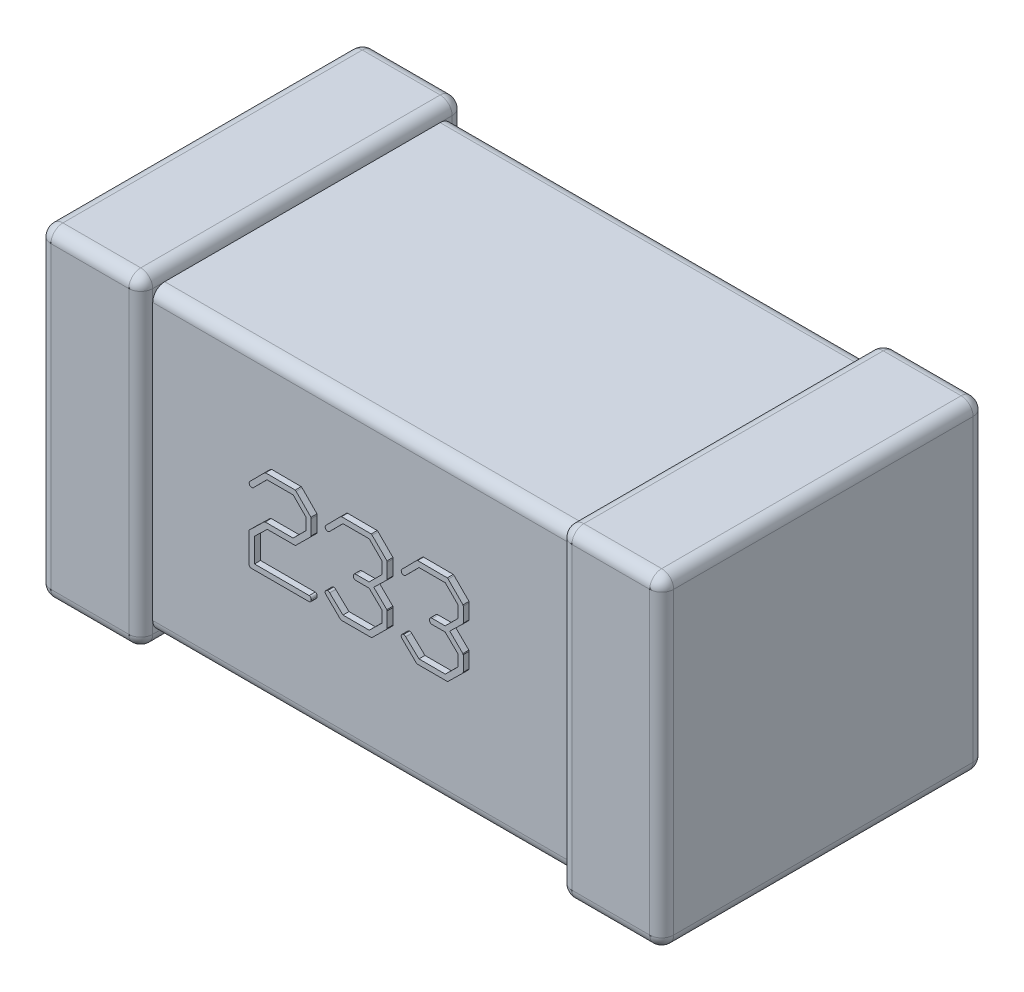
SolidWorks part; units mm, degrees
ref_plane "Front Plane" through (0, 0, 0) normal (0, 0, 1) x (1, 0, 0)
ref_plane "Top Plane" through (0, 0, 0) normal (0, 1, 0) x (1, 0, 0)
ref_plane "Right Plane" through (0, 0, 0) normal (1, 0, 0) x (0, 0, -1)
sketch "Sketch2" plane through (0, 0, 0) normal (0, 1, 0) x (1, 0, 0)
  line L1 (0, 0) -> (1, 0)
  line L2 (0, 0) -> (0, 0.5)
  line L3 (0, 0.5) -> (1, 0.5)
  line L4 (1, 0) -> (1, 0.5)
  dimension "D1" = 1
  dimension "D2" = 0.5
extrude "Boss-Extrude1" add sketch "Sketch2" along normal blind 0.5 contours L3 L4 L1 L2
fillet "Fillet3" radius 0.02 12 edges at (0, 0, -0.25) (0.5, 0, -0.5) (1, 0, -0.25) (0.5, 0, 0) (0, 0.5, -0.25) (0.5, 0.5, -0.5) (1, 0.5, -0.25) (0.5, 0.5, 0) (0, 0.25, -0.5) (1, 0.25, -0.5) (1, 0.25, 0) (0, 0.25, 0)
sketch "Sketch3" plane through (0, 0, 0) normal (0, 0, 1) x (1, 0, 0)
  line L1 (-0.02, 0.52) -> (0.15, 0.52)
  line L2 (-0.02, 0.52) -> (-0.02, -0.02)
  line L3 (-0.02, -0.02) -> (0.15, -0.02)
  line L4 (0.15, 0.52) -> (0.15, -0.02)
  point P4 (0, 0)
  dimension "D1" = 0.54
  dimension "D2" = 0.17
extrude "Boss-Extrude3" add sketch "Sketch3" along normal blind 0.02 and the other way blind 0.52 separate body
fillet "Fillet4" radius 0.02 12 edges at (-0.02, 0.52, -0.25) (0.15, 0.52, -0.25) (-0.02, -0.02, -0.25) (0.15, -0.02, -0.25) (0.065, -0.02, -0.52) (0.15, 0.25, -0.52) (0.065, 0.52, -0.52) (-0.02, 0.25, -0.52) (0.065, 0.52, 0.02) (0.15, 0.25, 0.02) (0.065, -0.02, 0.02) (-0.02, 0.25, 0.02)
move or copy body "Body-Move/Copy1" bodies to move or copy 103 copy yes number of copies 1 translate (0.87, 0, 0)
sketch "Sketch4" plane through (0, 0, 0) normal (0, 0, 1) x (1, 0, 0)
  text T0 "233" font "SWMono" height 0.15
extrude "Boss-Extrude4" add sketch "Sketch4" along normal blind 0.01 separate body
